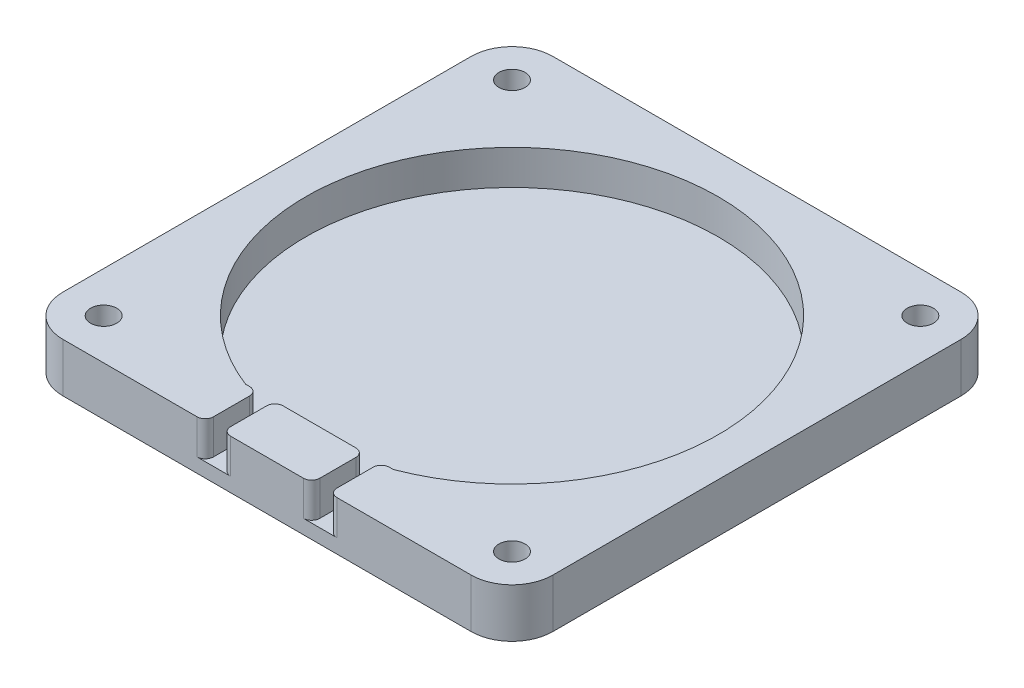
SolidWorks part; units mm, degrees
material "PLA"
ref_plane "Front Plane" through (0, 0, 0) normal (0, 0, 1) x (1, 0, 0)
ref_plane "Top Plane" through (0, 0, 0) normal (0, 1, 0) x (1, 0, 0)
ref_plane "Right Plane" through (0, 0, 0) normal (1, 0, 0) x (0, 0, -1)
other "Configuration Table"
sketch "Sketch1" plane through (0, 0, 0) normal (0, 1, 0) x (1, 0, 0)
  line L0 (-9, -23.3238) -> (9, -23.3238) construction
  line L1 (-9.0464, -23.5738) -> (9.0464, -23.5738)
  line L3 (-30, -30) -> (30, -30)
  line L4 (-30, -30) -> (-30, 30)
  line L5 (-30, 30) -> (30, 30)
  line L6 (-23, -1) -> (-24.98, -1)
  line L7 (-23, 1) -> (-23, -1)
  line L8 (-24.98, 1) -> (-23, 1)
  line L9 (9, -23) -> (9, -23.3238)
  line L10 (-9, -23) -> (9, -23)
  line L11 (-9, -23.3238) -> (-9, -23)
  line L18 (30, -30) -> (30, 30)
  line L19 (-30, -30) -> (30, 30) construction
  line L20 (-30, 30) -> (30, -30) construction
  arc A0 (9.0464, -23.5738) -> (-25.2298, 1.01) centre (0, 0) ccw
  arc A1 (-25.2298, 1.01) -> (-9.0464, -23.5738) centre (0, 0) ccw
  arc A2 (-24.98, -1) -> (-9, -23.3238) centre (0, 0) ccw
  arc A3 (9, -23.3238) -> (-24.98, 1) centre (0, 0) ccw
  arc A4 (-24.98, 1) -> (-9, -23.3238) centre (0, 0) ccw construction
  arc A5 (9, -23.3238) -> (-24.98, 1) centre (0, 0) ccw construction
  dimension "D2" = 0.25
  dimension "D3" = 60
  dimension "D1" = 0
extrude "Boss-Extrude1" add sketch "Sketch1" along normal up to surface (4.2575 mm away)
sketch "Sketch2" plane through (0, 0, 0) normal (0, -1, 0) x (1, 0, 0)
  line L4 (30, -30) -> (30, 30)
  line L5 (30, 30) -> (-30, 30)
  line L6 (-30, 30) -> (-30, -30)
  line L7 (-30, -30) -> (30, -30)
  line L8 (30, -30) -> (30, 30)
  line L9 (30, 30) -> (-30, 30)
  line L10 (-30, 30) -> (-30, -30)
  line L11 (-30, -30) -> (30, -30)
  dimension "D1" = 0
extrude "Boss-Extrude2" add sketch "Sketch2" along normal offset from surface (1.7425 mm away) 6 up to face at (0, 4.2575, -0.8381)
sketch "Sketch3" plane through (0, 4.2575, 0) normal (0, 1, 0) x (1, 0, 0)
  line L0 (-7.56, -25.9382) -> (-7.56, -47.65) construction
  line L1 (-7.56, -46.4548) -> (-5.4643, -46.4548)
  line L2 (-7.56, -46.4548) -> (-7.56, -22.9957)
  line L3 (-7.56, -22.9957) -> (-5.4643, -22.9957)
  line L4 (-5.4643, -46.4548) -> (-5.4643, -22.9957)
  line L6 (0, 0) -> (0, -68.3335) construction
  line L7 (7.56, -22.9957) -> (5.4643, -22.9957)
  line L8 (5.4643, -46.4548) -> (5.4643, -22.9957)
  line L9 (7.56, -46.4548) -> (5.4643, -46.4548)
  line L10 (7.56, -46.4548) -> (7.56, -22.9957)
extrude "Cut-Extrude1" cut sketch "Sketch3" against normal up to surface (4.2575 mm away) up to face at (0, 0, -0.8381)
fillet "Fillet1" radius 1 8 edges at (7.56, 2.1287, 30) (5.4643, 2.1287, 30) (7.56, 2.1287, 23.5738) (5.4643, 2.1287, 23.5738) (-5.4643, 2.1287, 23.5738) (-7.56, 2.1287, 23.5738) (-5.4643, 2.1287, 30) (-7.56, 2.1287, 30)
fillet "Fillet2" radius 5 4 edges at (-30, 1.2575, -30) (-30, 1.2575, 30) (30, 1.2575, -30) (30, 1.2575, 30)
sketch "Sketch4" plane through (0, -1.7425, 0) normal (0, -1, 0) x (1, 0, 0)
  line L1 (-25, -25) -> (25, -25)
  line L2 (-25, -25) -> (-25, 25)
  line L3 (-25, 25) -> (25, 25)
  line L4 (25, -25) -> (25, 25)
  line L5 (-25, -25) -> (25, 25) construction
  line L6 (-25, 25) -> (25, -25) construction
  point P0 (0, 0)
  dimension "D1" = 50
hole_wizard "M3 Clearance Hole1" positions "Sketch7" profile "Sketch8" hole size "M3" standard "ANSI Metric" end condition through all
sketch "Sketch7" plane through (0, -1.7425, 0) normal (0, -1, 0) x (-1, 0, 0)
  point P0 (-25, 25)
  point P3 (25, 25)
  point P6 (25, -25)
  point P9 (-25, -25)
sketch "Sketch8" plane through (25, -1.7425, -25) normal (1, 0, 0) x (0, 0, -1)
  line L0 (0, 0) -> (0, 6)
  line L1 (0, 6) -> (1.6, 6)
  line L2 (1.6, 6) -> (1.6, 0)
  line L5 (1.6, 0) -> (0, 0)
  line L11 (0, -6.35) -> (0, 107.95) construction
  dimension "Thru Hole Dia." = 3.2
  dimension "Thru Hole Depth" = 6
